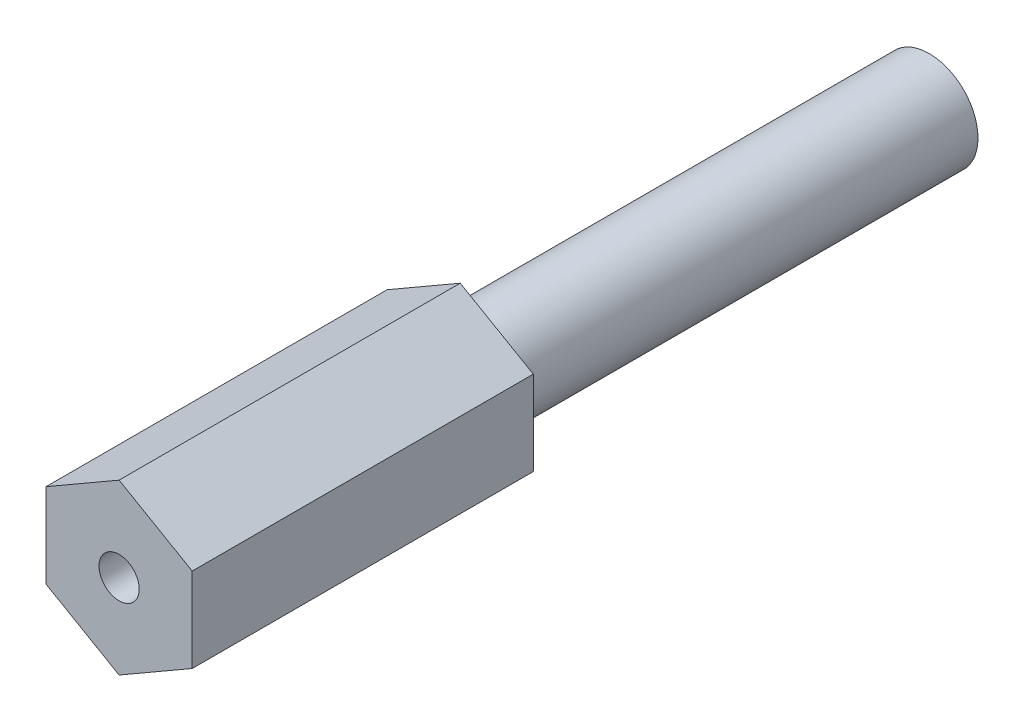
SolidWorks part; units mm, degrees
material "Acier non allié"
ref_plane "Plan1" through (0, 0, 0) normal (0, 0, 1) x (1, 0, 0)
ref_plane "Plan2" through (0, 0, 0) normal (0, 1, 0) x (1, 0, 0)
ref_plane "Plan3" through (0, 0, 0) normal (1, 0, 0) x (0, 0, -1)
sketch "Esquisse1" plane through (0, 0, 0) normal (0, 0, 1) x (1, 0, 0)
  line L1 (0, 6.9282) -> (-6, 3.4641)
  line L2 (-6, 3.4641) -> (-6, -3.4641)
  line L3 (-6, -3.4641) -> (0, -6.9282)
  line L4 (0, -6.9282) -> (6, -3.4641)
  line L5 (6, -3.4641) -> (6, 3.4641)
  line L6 (6, 3.4641) -> (0, 6.9282)
  circle A0 centre (0, 0) radius 6 construction
  dimension "D1" = 12
extrude "Base-Extrusion" add sketch "Esquisse1" along normal blind 28
sketch "Esquisse2" plane through (0, 0, 0) normal (0, 0, -1) x (-1, 0, 0)
  circle A0 centre (0, 0) radius 4
  dimension "D1" = 8
extrude "Boss.-Extru.1" add sketch "Esquisse2" along normal blind 38.5
hole_wizard "Perçage1" positions "Esquisse6" profile "Esquisse5" tap size "M4x0.7" standard "ISO"
sketch "Esquisse6" plane through (0, 0, 28) normal (0, 0, 1) x (1, 0, 0)
  point P0 (0, 0)
cosmetic thread "Représentation de filetage1" parameters "D1"=25, "D2"=4
sketch "Esquisse5" plane through (0, 0, 28) normal (1, 0, 0) x (0, -1, 0)
  line L0 (0, 0) -> (0, 25.9914)
  line L1 (0, 25.9914) -> (1.65, 25)
  line L2 (1.65, 25) -> (1.65, 0)
  line L5 (1.65, 0) -> (0, 0)
  line L10 (0, 25.9914) -> (-1.65, 25) construction
  line L11 (0, -6.35) -> (0, 107.95) construction
  dimension "Diamètre du perçage" = 3.3
  dimension "Profondeur du perçage" = 25
  dimension "Angle de pointe" = 118
hole_wizard "Perçage2" positions "Esquisse8" profile "Esquisse7" tap size "M4x0.7" standard "ISO"
sketch "Esquisse8" plane through (0, 0, -38.5) normal (0, 0, -1) x (-1, 0, 0)
  point P0 (0, 0)
sketch "Esquisse7" plane through (0, 0, -38.5) normal (1, 0, 0) x (0, 1, 0)
  line L0 (0, 0) -> (0, 25.9914)
  line L1 (0, 25.9914) -> (1.65, 25)
  line L2 (1.65, 25) -> (1.65, 0)
  line L5 (1.65, 0) -> (0, 0)
  line L10 (0, 25.9914) -> (-1.65, 25) construction
  line L11 (0, -6.35) -> (0, 107.95) construction
  dimension "Diamètre du perçage" = 3.3
  dimension "Profondeur du perçage" = 25
  dimension "Angle de pointe" = 118
cosmetic thread "Représentation de filetage2" parameters "D1"=25, "D2"=4
